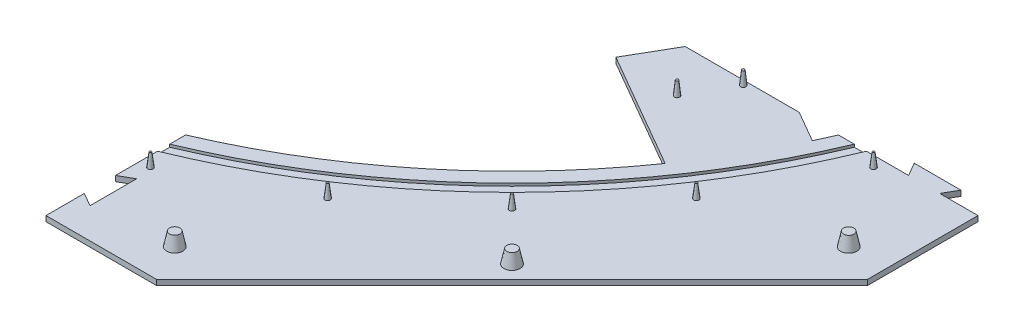
SolidWorks part; units mm, degrees
ref_plane "Front Plane" through (0, 0, 0) normal (0, 0, 1) x (1, 0, 0)
ref_plane "Top Plane" through (0, 0, 0) normal (0, 1, 0) x (1, 0, 0)
ref_plane "Right Plane" through (0, 0, 0) normal (1, 0, 0) x (0, 0, -1)
sketch "Sketch1" plane through (0, 0, 0) normal (0, 1, 0) x (1, 0, 0)
  line L7 (264, 0) -> (264, 131.98)
  line L9 (131.9796, 264) -> (0, 264)
  line L14 (131.9796, 264) -> (264, 131.98)
  line L15 (0, 264) -> (0, 0) construction
  line L16 (264, 109.3524) -> (186.6762, 186.6762) [skipped]
  line L17 (0, 0) -> (264, 0) construction
  line L18 (264, -131.9796) -> (131.98, -264)
  line L19 (-264, 0) -> (-264, -109.3524) [skipped]
  line L20 (-186.6762, 186.6762) -> (-264, 109.3524) [skipped]
  line L21 (-186.6762, -186.6762) -> (-109.3524, -264) [skipped]
  line L22 (0, -264) -> (109.3524, -264) [skipped]
  line L23 (186.6762, -186.6762) -> (264, -109.3524) [skipped]
  line L24 (264, -131.9796) -> (264, 0)
  line L25 (0, -264) -> (131.98, -264)
  line L26 (-131.9796, -264) -> (-264, -131.98)
  line L27 (-131.9796, -264) -> (0, -264)
  line L28 (-264, 0) -> (-264, -131.98)
  line L29 (-264, 131.9796) -> (-131.98, 264)
  line L30 (-264, 131.9796) -> (-264, 0)
  line L31 (0, 264) -> (-131.98, 264)
  arc A0 (264, 0) -> (0, 264) centre (0, 0) ccw construction
  point P33 (0, 0)
  dimension "D1" = 264
  dimension "D2" = 280
  dimension "D3" = 131.98
  dimension "D4" = 4
extrude "baseplate profile" add sketch "Sketch1" against normal blind 2
sketch "Sketch2" plane through (0, 0, 0) normal (0, 1, 0) x (1, 0, 0)
  line L0 (0, -248) -> (0, 248) construction
  circle A0 centre (0, 248) radius 1
  dimension "D2" = 2
  dimension "D1" = 496
extrude "M3 pins" add sketch "Sketch2" along normal blind 5 draft 7
sketch "center line" plane through (0, 0, 0) normal (0, 0, 1) x (1, 0, 0)
  line L0 (0, 0) -> (0, 200) construction
  dimension "D1" = 200
pattern_circular "CirPattern1" count 32 over 360 about axis through (0, 0, 0) along (0, 1, 0) of "M3 pins"
sketch "Sketch4" plane through (0, 0, 0) normal (0, 1, 0) x (1, 0, 0)
  line L0 (0, 0) -> (0, 201) construction
  line L1 (-9, 201) -> (9, 201) construction
  circle A0 centre (9, 201) radius 1
  circle A1 centre (-9, 201) radius 1
  point P5 (0, 201)
  dimension "D3" = 2
  dimension "D4" = 2
  dimension "D1" = 201
  dimension "D2" = 18
extrude "pillar pins" add sketch "Sketch4" along normal blind 5 draft 6
pattern_circular "CirPattern2" count 6 over 360 about axis through (0, 0, 0) along (0, 1, 0) of "pillar pins"
sketch "Sketch5" plane through (0, 0, 0) normal (0, 1, 0) x (1, 0, 0)
  line L0 (-193.0402, 193.0402) -> (193.0402, -193.0402) construction
  line L1 (-131.9796, -264) -> (131.98, -264) construction
  circle A0 centre (-193.0402, 193.0402) radius 3
  dimension "D3" = 6
  dimension "D1" = 546
  dimension "D2" = 45
extrude "M8 hole -1" add sketch "Sketch5" along normal blind 5 draft 12
pattern_circular "M8 -1 pattern" count 4 over 360 about axis through (0, 0, 0) along (0, 1, 0) of "M8 hole -1"
sketch "Sketch6" plane through (0, 0, 0) normal (0, 1, 0) x (1, 0, 0)
  line L0 (0, 0) -> (0, -324.5462) construction
  line L1 (0, 0) -> (-438.1399, 0) construction
  circle A0 centre (-125, -250) radius 3
  dimension "D1" = 6
  dimension "D2" = 125
  dimension "D3" = 250
extrude "M8 -2" add sketch "Sketch6" along normal blind 5 draft 12
pattern_circular "M8 -2 pattern" count 4 over 360 about axis through (0, 0, 0) along (0, 1, 0) of "M8 -2"
pattern_circular "M8 -3" count 2 over 36.9 about axis through (0, 0, 0) along (0, 1, 0) of "M8 -2 pattern", "M8 -2"
sketch "Sketch7" [suppressed] plane through (0, 0, 0) normal (0, 1, 0) x (1, 0, 0)
  line L1 (94.9211, 86.9806) -> (274.9211, 86.9806)
  line L2 (94.9211, 86.9806) -> (94.9211, -93.0194)
  line L3 (94.9211, -93.0194) -> (274.9211, -93.0194)
  line L4 (274.9211, 86.9806) -> (274.9211, -93.0194)
  dimension "D1" = 180
  dimension "D2" = 180
sketch "Sketch8" plane through (0, 0, 0) normal (0, 1, 0) x (1, 0, 0)
  line L0 (0, 0) -> (0, -180) construction
  line L1 (20, -230) -> (-20, -230)
  line L2 (20, -230) -> (20, -180)
  line L3 (20, -180) -> (-20, -180)
  line L4 (-20, -230) -> (-20, -180)
  line L5 (0, 0) -> (115.434, -199.9375)
  line L6 (0, 0) -> (-115.434, -199.9375)
  arc A0 (20, -230) -> (115.434, -199.9375) centre (0, 0) ccw
  arc A1 (-20, -230) -> (-115.434, -199.9375) centre (0, 0) cw
  point P7 (0, -180)
  dimension "D4" = 30
  dimension "D1" = 40
  dimension "D2" = 180
  dimension "D3" = 50
extrude "cut center" cut sketch "Sketch8" against normal through all contours L5 L0 L3 L2 A0 | L0 L6 A1 L4 L3
pattern_circular "CirPattern7" count 6 over 360 about axis through (0, 0, 0) along (0, 1, 0) of "cut center"
sketch "middle piece space " plane through (0, 0, 0) normal (0, 1, 0) x (1, 0, 0)
  line L0 (0, 0) -> (-200, 0) construction
  line L1 (91, 110) -> (-91, 110)
  line L2 (-110, 91) -> (-290, 91)
  line L3 (-110, 91) -> (-110, -91)
  line L4 (-110, -91) -> (-290, -91)
  line L5 (-290, 91) -> (-290, -91)
  line L6 (-110, 91) -> (-290, -91) construction
  line L7 (-110, -91) -> (-290, 91) construction
  line L8 (91, 110) -> (91, 290)
  line L9 (91, 290) -> (-91, 290)
  line L10 (-91, 110) -> (-91, 290)
  line L11 (110, -91) -> (110, 91)
  line L12 (110, -91) -> (290, -91)
  line L13 (290, -91) -> (290, 91)
  line L14 (110, 91) -> (290, 91)
  line L15 (-91, -110) -> (91, -110)
  line L16 (-91, -110) -> (-91, -290)
  line L17 (-91, -290) -> (91, -290)
  line L18 (91, -110) -> (91, -290)
  point P22 (0, 0)
  dimension "D1" = 182
  dimension "D2" = 200
  dimension "D3" = 180
  dimension "D4" = 4
sketch "Sketch11" plane through (0, 0, 0) normal (0, 1, 0) x (1, 0, 0)
  line L0 (-131.9796, -264) -> (131.98, -264) construction
  line L1 (-91, -91) -> (-264, -91)
  line L2 (-91, -91) -> (-91, -264)
  line L3 (-91, -264) -> (-264, -264)
  line L4 (-264, -91) -> (-264, -264)
  line L5 (-264, 131.9796) -> (-264, -131.98) construction
  line L6 (-110, -91) -> (-290, -91) construction
  line L7 (-91, -110) -> (-91, -290) construction
sketch "Sketch13" plane through (0, -2, 0) normal (0, -1, 0) x (1, 0, 0)
  line L1 (295.8455, -414.0765) -> (-305.4926, -414.0765)
  line L2 (295.8455, -414.0765) -> (295.8455, 361.6153)
  line L3 (295.8455, 361.6153) -> (-305.4926, 361.6153)
  line L4 (-305.4926, -414.0765) -> (-305.4926, 361.6153)
  line L5 (-91, 91) -> (-264, 91)
  line L6 (-91, 91) -> (-91, 264)
  line L7 (-91, 264) -> (-264, 264)
  line L8 (-264, 91) -> (-264, 264)
extrude "Cut-Extrude2" [suppressed] cut sketch "Sketch13" against normal blind 10
sketch "Sketch14" plane through (0, 0, 0) normal (0, 1, 0) x (1, 0, 0)
  line L4 (-106, -244) -> (-83.5, -256.9904)
  line L5 (-83.5, -256.9904) -> (-83.5, -231.0096)
  line L6 (-83.5, -231.0096) -> (-106, -244)
  line L7 (-91, -264) -> (-264, -264) construction
  line L8 (-91, -110) -> (-91, -290) construction
  circle A0 centre (-91, -244) radius 7.5 construction
  dimension "D2" = 15
  dimension "D3" = 20
extrude "Boss-Extrude1" [suppressed] add sketch "Sketch14" against normal up to surface (2 mm away)
sketch "Sketch15" plane through (0, 0, 0) normal (0, 1, 0) x (1, 0, 0)
  line L0 (-110, -91) -> (-290, -91) construction
  line L1 (-256.9904, -98.5) -> (-231.0096, -98.5)
  line L2 (-231.0096, -98.5) -> (-244, -76)
  line L3 (-244, -76) -> (-256.9904, -98.5)
  line L4 (-264, -91) -> (-264, -264) construction
  circle A0 centre (-244, -91) radius 7.5 construction
  dimension "D1" = 15
  dimension "D2" = 20
extrude "Cut-Extrude3" [suppressed] cut sketch "Sketch15" against normal through all
sketch "Sketch16" plane through (0, -2, 0) normal (0, -1, 0) x (1, 0, 0)
  line L0 (110, 91) -> (290, 91) construction
  line L1 (91, 290) -> (290, 290)
  line L2 (91, 290) -> (91, 91)
  line L3 (91, 91) -> (290, 91)
  line L4 (290, 290) -> (290, 91)
  line L5 (91, 110) -> (91, 290) construction
  line L6 (-91, 290) -> (91, 290) construction
  line L7 (290, 91) -> (290, -91) construction
  line L9 (365.1131, -507.1986) -> (-340.9024, -507.1986)
  line L10 (365.1131, -507.1986) -> (365.1131, 455.048)
  line L11 (365.1131, 455.048) -> (-340.9024, 455.048)
  line L12 (-340.9024, -507.1986) -> (-340.9024, 455.048)
extrude "Cut-Extrude4" cut sketch "Sketch16" against normal through all
sketch "Sketch17" plane through (0, 0, 0) normal (0, 1, 0) x (1, 0, 0)
  line L0 (91, -264) -> (131.98, -264) construction
  line L1 (81, -244) -> (96, -252.6603)
  line L2 (96, -252.6603) -> (96, -235.3397)
  line L3 (96, -235.3397) -> (81, -244)
  line L4 (91, -110) -> (91, -290) construction
  circle A0 centre (91, -244) radius 5 construction
  dimension "D1" = 10
  dimension "D2" = 20
extrude "Cut-Extrude5" cut sketch "Sketch17" against normal through all
sketch "Sketch19" plane through (0, -2, 0) normal (0, -1, 0) x (-1, 0, 0)
  line L0 (-212.1768, -91) -> (-264, -91) construction
  line L1 (-235.3397, -86) -> (-252.6603, -86)
  line L2 (-252.6603, -86) -> (-244, -101)
  line L3 (-244, -101) -> (-235.3397, -86)
  line L4 (-264, -131.9796) -> (-264, -91) construction
  circle A0 centre (-244, -91) radius 5 construction
  dimension "D1" = 10
  dimension "D2" = 20
extrude "Boss-Extrude3" add sketch "Sketch19" against normal up to surface (2 mm away) contours L1 L2 L3 up to face at (155.3962, 0, 170.4232)
sketch "Sketch20" plane through (0, 0, 0) normal (0, 1, 0) x (1, 0, 0)
  circle A0 centre (0, 0) radius 236.3
  circle A1 centre (0, 0) radius 240.5
  dimension "D1" = 472.6
  dimension "D2" = 481
extrude "Cut-Extrude6" cut sketch "Sketch20" against normal blind 1
